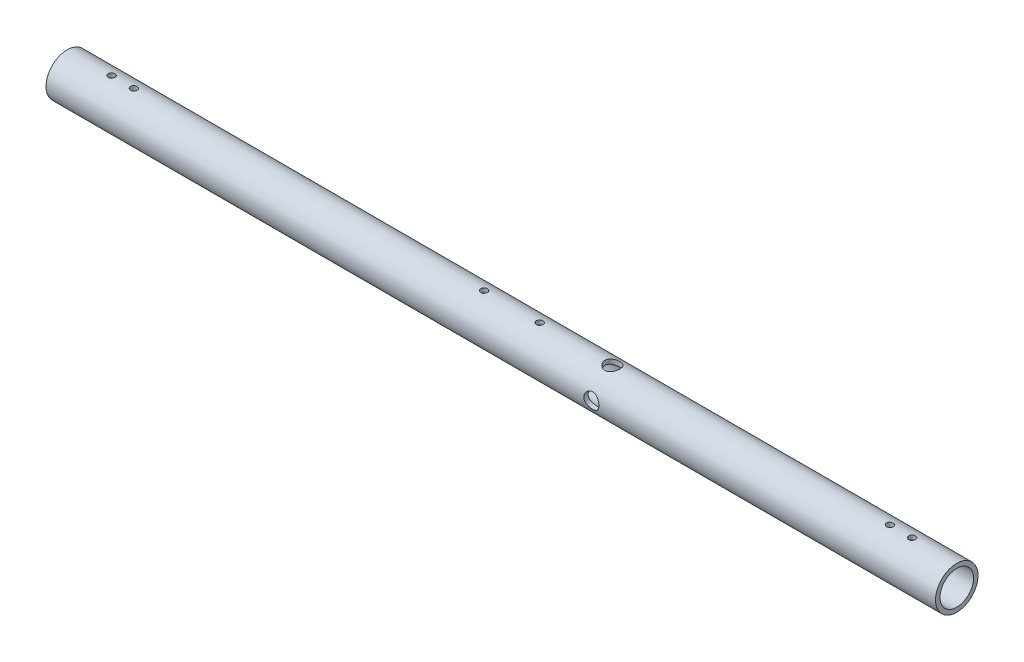
SolidWorks part; units mm, degrees
material "Aleación 6061"
ref_plane "Alzado" through (0, 0, 0) normal (0, 0, 1) x (1, 0, 0)
ref_plane "Planta" through (0, 0, 0) normal (0, 1, 0) x (1, 0, 0)
ref_plane "Vista lateral" through (0, 0, 0) normal (1, 0, 0) x (0, 0, -1)
sketch "Croquis1" plane through (0, 0, 0) normal (0, 0, 1) x (1, 0, 0)
  line L0 (200, 0) -> (-200, 0) construction
  line L1 (-200, 7.55) -> (200, 7.55)
  line L2 (200, 7.55) -> (200, 9.55)
  line L3 (200, 9.55) -> (-200, 9.55)
  line L4 (-200, 9.55) -> (-200, 7.55)
  point P16 (0, 0)
  dimension "D1" = 400
  dimension "D2" = 19.1
  dimension "D3" = 2
revolve "Revolución1" add sketch "Croquis1" angle 360 about L0
sketch "Croquis2" plane through (0, 0, 0) normal (0, 1, 0) x (1, 0, 0)
  line L0 (-200, 9.55) -> (-200, -9.55) construction
  line L1 (200, -9.55) -> (200, 9.55) construction
  line L2 (45.21, 0) -> (48.61, 0) construction
  line L3 (45.21, 0) -> (41.81, 0) construction
  circle A0 centre (-180, 0) radius 1.5
  circle A1 centre (180, 0) radius 1.5
  circle A2 centre (-12.5, 0) radius 1.5
  circle A3 centre (12.5, 0) radius 1.5
  circle A4 centre (-170, 0) radius 1.5
  circle A5 centre (170, 0) radius 1.5
  circle A6 centre (45.21, 0) radius 3.4
  dimension "D1" = 3
  dimension "D6" = 10
  dimension "D9" = 6.8
  dimension "D2" = 20
  dimension "D3" = 20
  dimension "D4" = 25
  dimension "D5" = 12.5
  dimension "D7" = 10
  dimension "D8" = 41.81
extrude "Cortar-Extruir1" cut sketch "Croquis2" against normal through all and the other way through all
sketch "Croquis3" plane through (0, 0, 0) normal (0, 0, 1) x (1, 0, 0)
  line L0 (45.21, 0) -> (41.81, 0) construction
  circle A0 centre (45.21, 0) radius 3.4
  dimension "D2" = 6.8
  dimension "D1" = 41.81
extrude "Cortar-Extruir2" cut sketch "Croquis3" along normal through all
